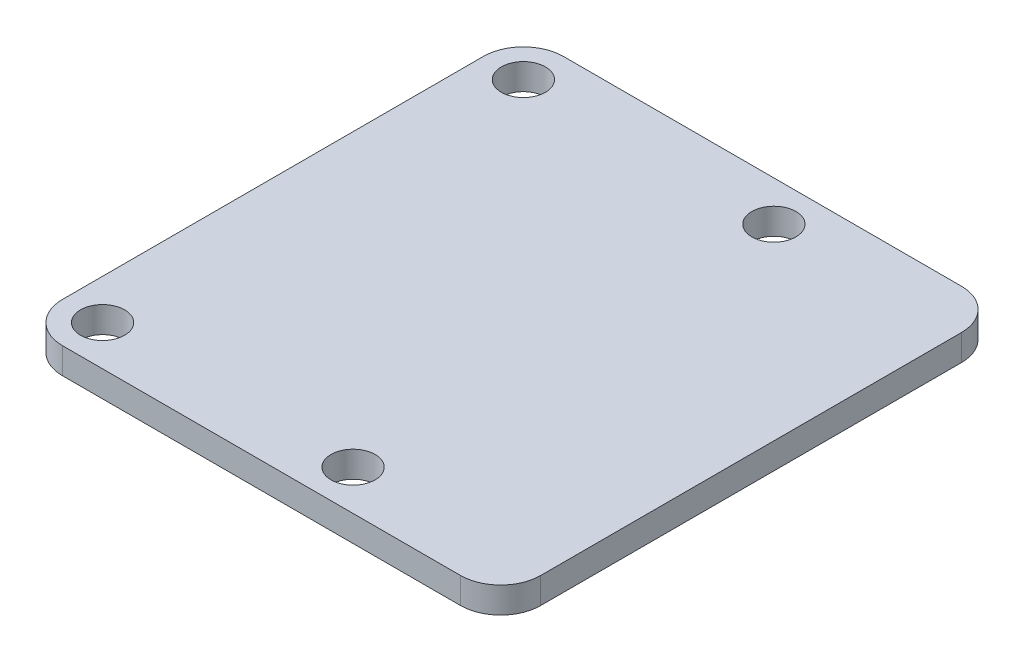
SolidWorks part; units mm, degrees
ref_plane "Front" through (0, 0, 0) normal (0, 0, 1) x (1, 0, 0)
ref_plane "Top" through (0, 0, 0) normal (0, 1, 0) x (1, 0, 0)
ref_plane "Right" through (0, 0, 0) normal (1, 0, 0) x (0, 0, -1)
sketch "Sketch1" plane through (0, 0, 0) normal (0, 1, 0) x (1, 0, 0)
  line L1 (-11.931, 12.5) -> (11.931, 12.5)
  line L2 (-11.931, 12.5) -> (-11.931, -12.5)
  line L3 (-11.931, -12.5) -> (11.931, -12.5)
  line L4 (11.931, 12.5) -> (11.931, -12.5)
  line L5 (-11.931, 12.5) -> (11.931, -12.5) construction
  line L6 (-11.931, -12.5) -> (11.931, 12.5) construction
  line L7 (-9.931, 10.5) -> (2.569, 10.5) construction
  line L8 (-9.931, 10.5) -> (-9.931, -10.5) construction
  line L9 (-9.931, -10.5) -> (2.569, -10.5) construction
  line L10 (2.569, 10.5) -> (2.569, -10.5) construction
  circle A0 centre (-9.931, -10.5) radius 1.1
  circle A1 centre (2.569, -10.5) radius 1.1
  circle A2 centre (-9.931, 10.5) radius 1.1
  circle A3 centre (2.569, 10.5) radius 1.1
  point P0 (0, 0)
  dimension "D7" = 2.2
  dimension "D1" = 25
  dimension "D2" = 23.862
  dimension "D3" = 2
  dimension "D4" = 2
  dimension "D5" = 2
  dimension "D6" = 14.5
extrude "Boss-Extrude1" add sketch "Sketch1" along normal blind 1.3
sketch "Sketch2" plane through (0, 0, 0) normal (0, -1, 0) x (1, 0, 0)
  line L0 (-11.931, 12.5) -> (11.931, 12.5) construction
  line L1 (-1.531, -4) -> (6.469, -4)
  line L2 (-1.531, -4) -> (-1.531, 4)
  line L3 (-1.531, 4) -> (6.469, 4)
  line L4 (6.469, -4) -> (6.469, 4)
  line L5 (-1.531, -4) -> (6.469, 4) construction
  line L6 (-1.531, 4) -> (6.469, -4) construction
  line L7 (11.931, 12.5) -> (11.931, -12.5) construction
  point P0 (2.469, 0)
  dimension "D1" = 12.5
  dimension "D2" = 9.462
  dimension "D3" = 8
extrude "Boss-Extrude2" add sketch "Sketch2" along normal blind 2
sketch "Sketch3" plane through (0, -2, 0) normal (0, -1, 0) x (1, 0, 0)
  line L1 (-1.531, 4) -> (6.469, 4) construction
  line L2 (-1.531, 4) -> (-1.531, -4) construction
  line L3 (-1.531, -4) -> (6.469, -4) construction
  line L4 (6.469, 4) -> (6.469, -4) construction
  line L5 (-1.531, 4) -> (6.469, -4) construction
  line L6 (-1.531, -4) -> (6.469, 4) construction
  circle A0 centre (2.469, 0) radius 3.5
  point P0 (2.469, 0)
  dimension "D1" = 7
extrude "Boss-Extrude3" add sketch "Sketch3" along normal blind 2
fillet "Fillet1" radius 2 4 edges at (11.931, 0.65, -12.5) (-11.931, 0.65, -12.5) (-11.931, 0.65, 12.5) (11.931, 0.65, 12.5)
